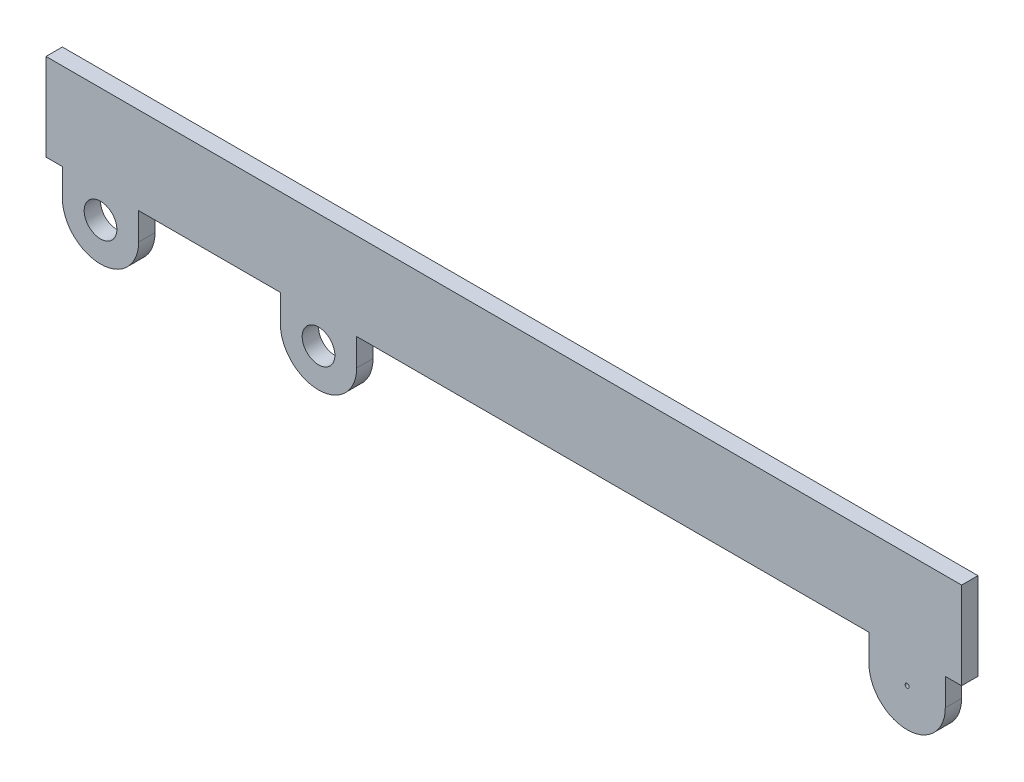
SolidWorks part; units mm, degrees
material "Pine"
ref_plane "Front Plane" through (0, 0, 0) normal (0, 0, 1) x (1, 0, 0)
ref_plane "Top Plane" through (0, 0, 0) normal (0, 1, 0) x (1, 0, 0)
ref_plane "Right Plane" through (0, 0, 0) normal (1, 0, 0) x (0, 0, -1)
sketch "Sketch1" plane through (0, 0, 0) normal (0, 0, 1) x (1, 0, 0)
  line L1 (-533.4, -50.8) -> (533.4, -50.8)
  line L2 (-533.4, -50.8) -> (-533.4, 50.8)
  line L3 (-533.4, 50.8) -> (533.4, 50.8)
  line L4 (533.4, -50.8) -> (533.4, 50.8)
  line L5 (-533.4, -50.8) -> (533.4, 50.8) construction
  line L6 (-533.4, 50.8) -> (533.4, -50.8) construction
  point P0 (0, 0)
  dimension "D1" = 1066.8
  dimension "D2" = 101.6
extrude "Boss-Extrude1" add sketch "Sketch1" along normal blind 19.05
sketch "Sketch2" plane through (0, 0, 19.05) normal (0, 0, 1) x (1, 0, 0)
  line L0 (-533.4, -50.8) -> (533.4, -50.8) construction
  line L1 (-514.35, -50.8) -> (-425.45, -50.8)
  line L2 (-514.35, -50.8) -> (-514.35, -82.55)
  line L3 (-514.35, -82.55) -> (-425.45, -82.55) construction
  line L4 (-425.45, -50.8) -> (-425.45, -82.55)
  line L5 (-533.4, 50.8) -> (-533.4, -50.8) construction
  line L6 (533.4, -50.8) -> (533.4, 50.8) construction
  line L7 (514.35, -50.8) -> (425.45, -50.8)
  line L8 (514.35, -50.8) -> (514.35, -82.55)
  line L9 (514.35, -82.55) -> (425.45, -82.55) construction
  line L10 (425.45, -50.8) -> (425.45, -82.55)
  line L11 (-260.35, -50.8) -> (-171.45, -50.8)
  line L12 (-260.35, -50.8) -> (-260.35, -82.55)
  line L13 (-171.45, -50.8) -> (-171.45, -82.55)
  line L14 (-260.35, -82.55) -> (-171.45, -82.55) construction
  line L15 (-514.35, -50.8) -> (-260.35, -50.8) construction
  arc A0 (-514.35, -82.55) -> (-425.45, -82.55) centre (-469.9, -82.55) ccw
  circle A1 centre (-469.9, -82.55) radius 19.05
  arc A2 (514.35, -82.55) -> (425.45, -82.55) centre (469.9, -82.55) cw
  circle A4 centre (469.9, -82.55) radius 19.05 construction
  circle A5 centre (469.9, -82.55) radius 2.3813
  arc A6 (-260.35, -82.55) -> (-171.45, -82.55) centre (-215.9, -82.55) ccw
  circle A7 centre (-215.9, -82.55) radius 19.05
  point P13 (-469.9, -127)
  dimension "D4" = 38.1
  dimension "D6" = 4.7625
  dimension "D1" = 19.05
  dimension "D2" = 88.9
  dimension "D3" = 76.2
  dimension "D5" = 19.05
  dimension "D8" = 254
  dimension "D7" = 2
extrude "Boss-Extrude2" add sketch "Sketch2" against normal up to surface (19.05 mm away) up to face at (0, 0, 0)
sketch "Sketch4" plane through (0, 0, 0) normal (0, 0, -1) x (-1, 0, 0)
  line L0 (-514.35, -82.55) -> (-425.45, -82.55) construction
  circle A0 centre (-469.9, -82.55) radius 19.05
  circle A1 centre (-469.9, -82.55) radius 19.05 construction
extrude "Cut-Extrude1" cut sketch "Sketch4" against normal blind 9.525
